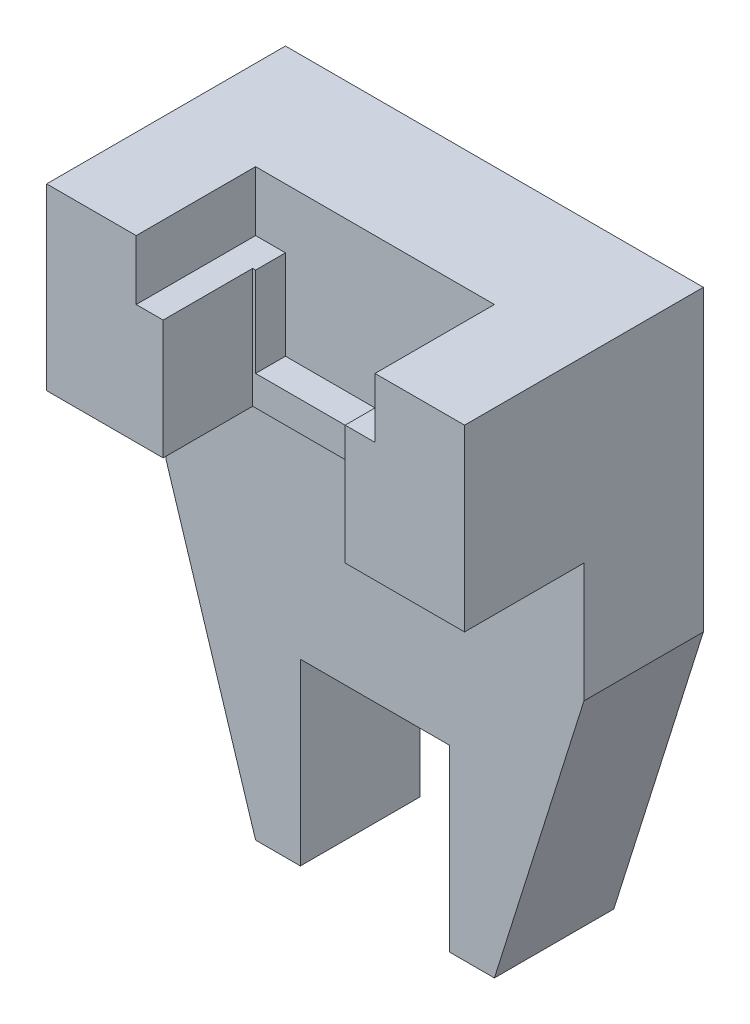
SolidWorks part; units mm, degrees
ref_plane "Front Plane" through (0, 0, 0) normal (0, 0, 1) x (1, 0, 0)
ref_plane "Top Plane" through (0, 0, 0) normal (0, 1, 0) x (1, 0, 0)
ref_plane "Right Plane" through (0, 0, 0) normal (1, 0, 0) x (0, 0, -1)
sketch "Sketch1" plane through (0, 0, 0) normal (0, 0, 1) x (1, 0, 0)
  line L10 (13.662, -3.5185) -> (13.662, -50003.5185) construction
  line L16 (26.162, -97.697) -> (26.162, -67.697)
  line L17 (33.662, -97.697) -> (26.162, -97.697)
  line L18 (48.662, 0) -> (-21.338, 0)
  line L19 (-21.338, 0) -> (-21.338, -50)
  line L20 (-21.338, -50) -> (-6.338, -97.697)
  line L21 (-6.338, -97.697) -> (1.162, -97.697)
  line L22 (1.162, -97.697) -> (1.162, -67.697)
  line L23 (1.162, -67.697) -> (26.162, -67.697)
  line L24 (48.662, -50) -> (33.662, -97.697)
  line L25 (48.662, 0) -> (48.662, -50)
  point P4 (13.662, -67.697)
  point P14 (13.662, 0)
  dimension "D1" = 35
  dimension "D2" = 50
  dimension "D3" = 50
  dimension "D4" = 67.697
  dimension "D5" = 30
  dimension "D6" = 12.5
extrude "Boss-Extrude1" add sketch "Sketch1" along normal blind 20 from offset 0 contours L23 L16 L17 L24 L25 L18 L19 L20 L21 L22
sketch "Sketch2" plane through (0, 0, 0) normal (0, 0, 1) x (1, 0, 0)
  line L0 (13.662, 1000) -> (13.662, 0) construction
  line L1 (48.662, 0) -> (-21.338, 0) construction
  line L3 (48.662, 0) -> (33.662, 0)
  line L14 (-21.338, 0) -> (-21.338, -10)
  line L22 (-21.338, 0) -> (-21.338, -50) construction
  line L23 (-21.338, -10) -> (-6.338, -10)
  line L26 (-6.338, -10) -> (-6.338, 0)
  line L27 (48.662, 0) -> (48.662, -10)
  line L28 (48.662, 0) -> (48.662, -50) construction
  line L29 (48.662, -10) -> (33.662, -10)
  line L30 (33.662, -10) -> (33.662, 0)
  line L31 (-6.338, 0) -> (-21.338, 0)
  line L32 (-21.338, -10) -> (49978.662, -10) construction
  point P4 (13.662, 0)
  dimension "D1" = 40
  dimension "D2" = 20
  dimension "D3" = 10
  dimension "D4" = 10
extrude "Boss-Extrude3" add sketch "Sketch2" along normal blind 40
sketch "Sketch4" plane through (0, 0, 0) normal (0, 0, 1) x (1, 0, 0)
  line L0 (-1021.338, -10) -> (-21.338, -10) construction
  line L1 (-21.338, -30) -> (48.662, -30)
  line L2 (33.662, 0) -> (-6.338, 0) construction
  line L3 (-21.338, -10) -> (-21.338, -30)
  line L4 (-21.338, -10) -> (-21.338, -50) construction
  line L14 (48.662, -10) -> (48.662, -30)
  line L17 (-21.338, -10) -> (-1.338, -10)
  line L19 (-1.338, -24.9992) -> (13.662, -24.9992)
  line L20 (13.662, -24.9992) -> (28.662, -24.9992)
  line L21 (48.662, -10) -> (49978.662, -10) construction
  line L25 (-1.338, -10) -> (-1.338, -24.9992)
  line L27 (28.662, -24.9992) -> (28.662, -10)
  line L28 (28.662, -10) -> (48.662, -10)
  point P8 (13.662, 0)
  dimension "D1" = 14.9992
  dimension "D2" = 15
  dimension "D3" = 20
  dimension "D4" = 15
  dimension "D5" = 70
extrude "Boss-Extrude5" add sketch "Sketch4" along normal blind 40
sketch "Sketch6" plane through (0, -30, 0) normal (0, -1, 0) x (1, 0, 0)
  line L0 (-21.338, 40) -> (48.662, 40) construction
  line L1 (-1.8278, 40) -> (28.1722, 40)
  line L2 (-1.8278, 40) -> (-1.8278, 25)
  line L3 (-1.8278, 25) -> (28.1722, 25)
  line L4 (28.1722, 40) -> (28.1722, 25)
  line L5 (13.1722, 40) -> (13.1722, 17.5073) construction
  dimension "D1" = 30
  dimension "D2" = 15
extrude "Cut-Extrude2" cut sketch "Sketch6" against normal blind 40
sketch "Sketch8" plane through (0, -30, 0) normal (0, -1, 0) x (1, 0, 0)
  line L1 (28.1722, 40) -> (28.6622, 40)
  line L2 (28.1722, 40) -> (28.1722, 25)
  line L3 (28.1722, 25) -> (28.6622, 25)
  line L4 (28.6622, 40) -> (28.6622, 25)
  point P5 (27.614, 43.7394)
  dimension "D1" = 0.49
  dimension "D2" = 15
extrude "Cut-Extrude4" cut sketch "Sketch8" against normal blind 40
